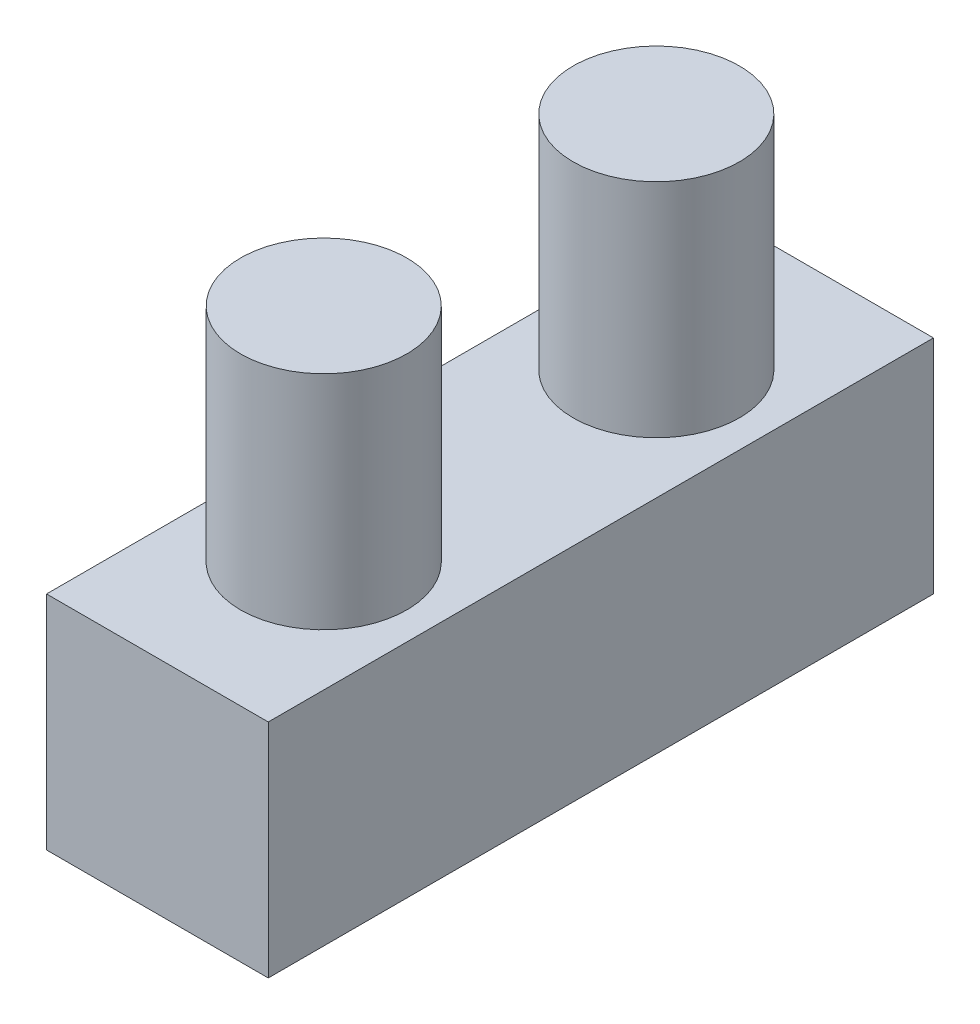
SolidWorks part; units mm, degrees
ref_plane "Front Plane" through (0, 0, 0) normal (0, 0, 1) x (1, 0, 0)
ref_plane "Top Plane" through (0, 0, 0) normal (0, 1, 0) x (1, 0, 0)
ref_plane "Right Plane" through (0, 0, 0) normal (1, 0, 0) x (0, 0, -1)
sketch "Sketch1" plane through (0, 0, 0) normal (0, 1, 0) x (1, 0, 0)
  line L1 (0, 0) -> (2, 0)
  line L2 (0, 0) -> (0, -6)
  line L3 (0, -6) -> (2, -6)
  line L4 (2, 0) -> (2, -6)
  dimension "D1" = 6
  dimension "D2" = 2
extrude "Boss-Extrude1" add sketch "Sketch1" along normal blind 2
sketch "Sketch2" plane through (0, 2, 0) normal (0, 1, 0) x (1, 0, 0)
  line L0 (2, 0) -> (0, 0) construction
  circle A0 centre (1, -1.5) radius 0.75
  circle A1 centre (1, -4.5) radius 0.75
  dimension "D2" = 1.5
  dimension "D3" = 1.5
  dimension "D1" = 3
  dimension "D4" = 1.5
extrude "Boss-Extrude2" add sketch "Sketch2" along normal blind 2
